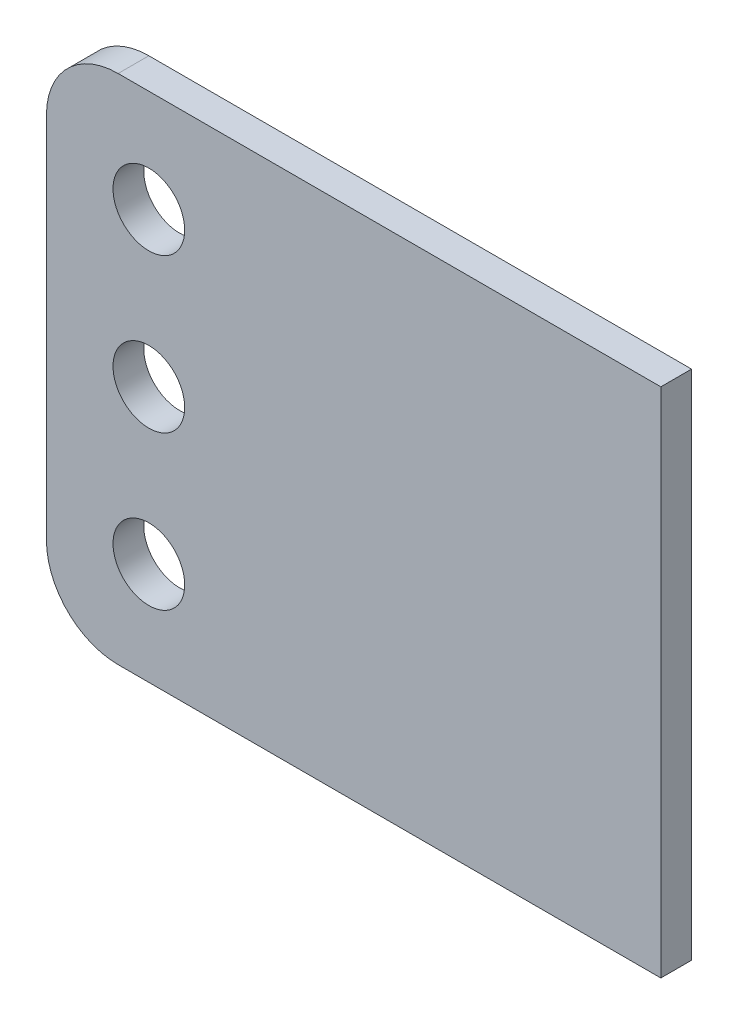
SolidWorks part; units mm, degrees
ref_plane "Plan de face" through (0, 0, 0) normal (0, 0, 1) x (1, 0, 0)
ref_plane "Plan de dessus" through (0, 0, 0) normal (0, 1, 0) x (1, 0, 0)
ref_plane "Plan de droite" through (0, 0, 0) normal (1, 0, 0) x (0, 0, -1)
sketch "Esquisse1" plane through (0, 0, 0) normal (0, 0, 1) x (1, 0, 0)
  line L1 (0, 0) -> (60, 0)
  line L2 (0, 0) -> (0, 50)
  line L3 (0, 50) -> (60, 50)
  line L4 (60, 0) -> (60, 50)
  dimension "D1" = 50
  dimension "D2" = 60
extrude "Boss.-Extru.1" add sketch "Esquisse1" along normal blind 3
sketch "Esquisse2" plane through (0, 0, 3) normal (0, 0, 1) x (1, 0, 0)
  line L0 (0, 50) -> (0, 0) construction
  line L1 (0, 0) -> (60, 0) construction
  circle A0 centre (10, 10) radius 3.5
  circle A1 centre (10, 25) radius 3.5
  circle A2 centre (10, 40) radius 3.5
  dimension "D1" = 7
  dimension "D2" = 7
  dimension "D3" = 7
  dimension "D4" = 10
  dimension "D5" = 10
  dimension "D6" = 10
  dimension "D7" = 10
  dimension "D8" = 25
  dimension "D9" = 40
extrude "Enlèv. mat.-Extru.1" cut sketch "Esquisse2" against normal blind 3
fillet "Congé1" radius 7 2 edges at (0, 0, 1.5) (0, 50, 1.5)
